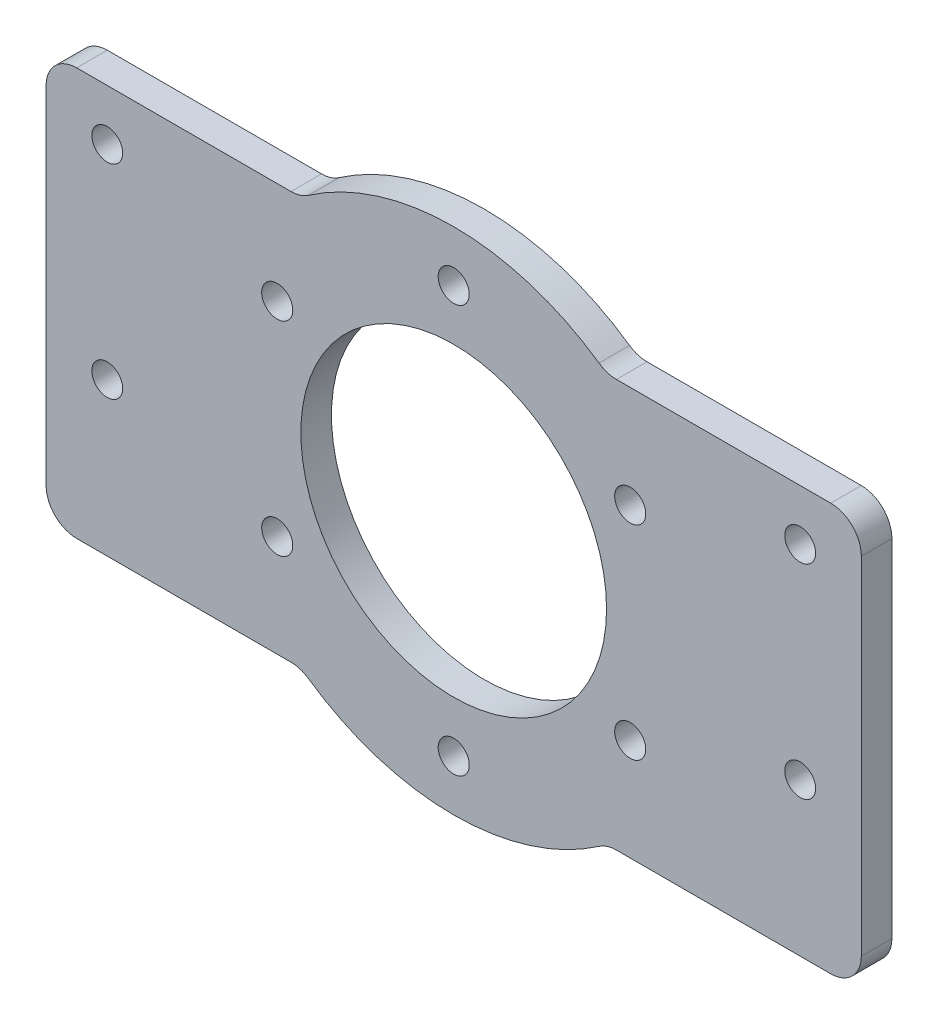
SolidWorks part; units mm, degrees
material "Thornel Mat VMA"
ref_plane "前视基准面" through (0, 0, 0) normal (0, 0, 1) x (1, 0, 0)
ref_plane "上视基准面" through (0, 0, 0) normal (0, 1, 0) x (1, 0, 0)
ref_plane "右视基准面" through (0, 0, 0) normal (1, 0, 0) x (0, 0, -1)
sketch "草图1" plane through (0, 0, 0) normal (0, 0, 1) x (1, 0, 0)
  circle A0 centre (0, 0) radius 20 construction
  circle A1 centre (0, 0) radius 25
  circle A2 centre (0, 20) radius 1.525
  circle A3 centre (17.3205, 10) radius 1.525
  circle A4 centre (17.3205, -10) radius 1.525
  circle A5 centre (0, -20) radius 1.525
  circle A6 centre (-17.3205, -10) radius 1.525
  circle A7 centre (-17.3205, 10) radius 1.525
  circle A8 centre (0, 0) radius 15
  point P15 (0, 0)
  dimension "D1" = 40
  dimension "D2" = 5
  dimension "D3" = 3.05
  dimension "D5" = 5
  dimension "D4" = 6
extrude "凸台-拉伸1" add sketch "草图1" along normal blind 3
sketch "草图3" plane through (0, 0, 3) normal (0, 0, 1) x (1, 0, 0)
  line L0 (15, 20) -> (40, 20)
  line L1 (-40, -20) -> (-15, -20)
  line L2 (-40, -20) -> (-40, 20)
  line L3 (-40, 20) -> (-15, 20)
  line L4 (40, -20) -> (40, 20)
  line L5 (0, 20) -> (0, -20) construction
  line L6 (-40, 0) -> (40, 0) construction
  line L7 (15, -20) -> (40, -20)
  circle A0 centre (0, 0) radius 25 construction
  arc A1 (15, -20) -> (15, 20) centre (0, 0) ccw
  arc A2 (-15, 20) -> (-15, -20) centre (0, 0) ccw
  point P0 (0, 0)
  dimension "D1" = 40
  dimension "D2" = 80
extrude "凸台-拉伸2" add sketch "草图3" against normal up to surface (3 mm away) up to face at (25, 0, 0)
fillet "圆角1" radius 3 8 edges at (-15, 20, 1.5) (-40, 20, 1.5) (15, -20, 1.5) (40, -20, 1.5) (40, 20, 1.5) (15, 20, 1.5) (-15, -20, 1.5) (-40, -20, 1.5)
sketch "草图4" plane through (0, 0, 3) normal (0, 0, 1) x (1, 0, 0)
  line L0 (0, 0) -> (0, 25) construction
  circle A0 centre (-34, -5) radius 1.25 construction
  circle A1 centre (-34, 15) radius 1.25 construction
  circle A2 centre (-34, -5) radius 1.25 construction
  circle A3 centre (-34, 15) radius 1.25 construction
  circle A4 centre (-34, 15) radius 1.515
  circle A5 centre (-34, -5) radius 1.515
  arc A6 (14.2578, 20.5357) -> (-14.2578, 20.5357) centre (0, 0) ccw construction
  circle A7 centre (34, 15) radius 1.25 construction
  circle A8 centre (34, -5) radius 1.25 construction
  circle A9 centre (34, -5) radius 1.515
  circle A10 centre (34, 15) radius 1.515
  dimension "D1" = 3.03
extrude "切除-拉伸1" cut sketch "草图4" against normal blind 10
